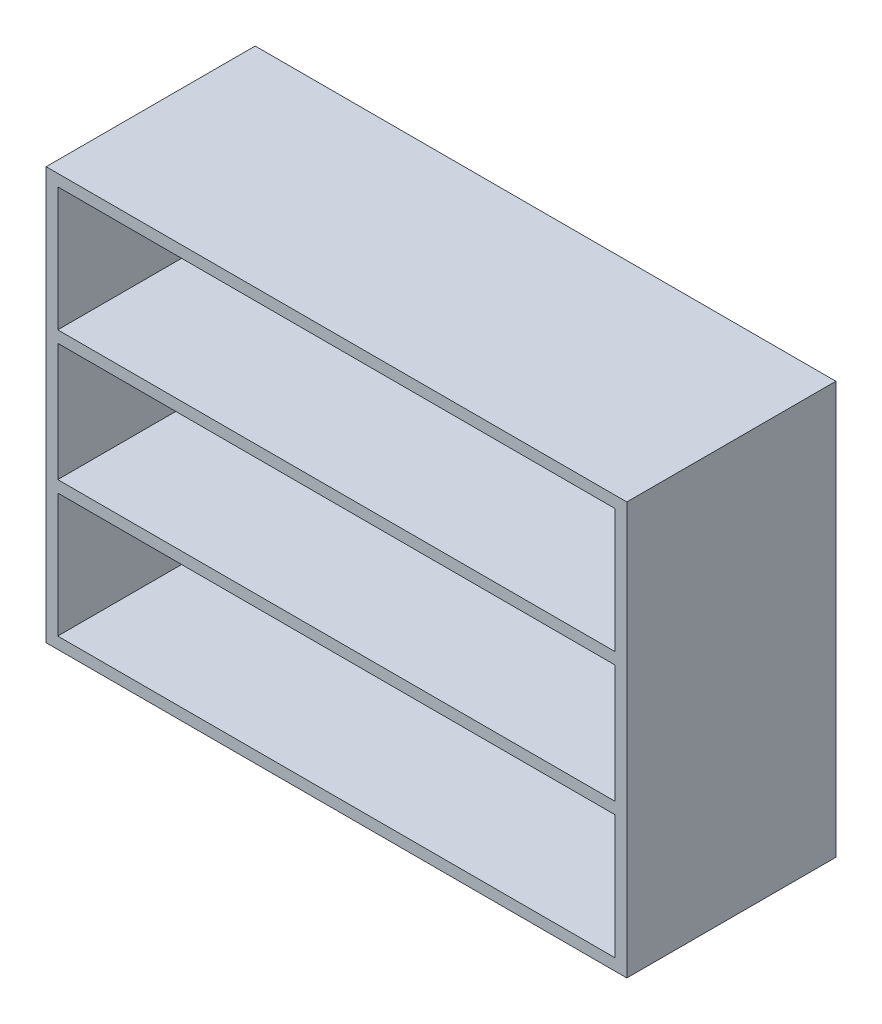
SolidWorks part; units mm, degrees
ref_plane "Front" through (0, 0, 0) normal (0, 0, 1) x (1, 0, 0)
ref_plane "Top" through (0, 0, 0) normal (0, 1, 0) x (1, 0, 0)
ref_plane "Right" through (0, 0, 0) normal (1, 0, 0) x (0, 0, -1)
sketch "Sketch1" plane through (0, 0, 0) normal (0, 1, 0) x (1, 0, 0)
  line L1 (-1270, 457.2) -> (1270, 457.2)
  line L2 (-1270, 457.2) -> (-1270, -457.2)
  line L3 (-1270, -457.2) -> (1270, -457.2)
  line L4 (1270, 457.2) -> (1270, -457.2)
  line L5 (-1270, 457.2) -> (1270, -457.2) construction
  line L6 (-1270, -457.2) -> (1270, 457.2) construction
  point P0 (0, 0)
  dimension "D1" = 2540
  dimension "D2" = 914.4
extrude "Boss-Extrude1" add sketch "Sketch1" along normal blind 1803.4
sketch "Sketch2" plane through (0, 0, 457.2) normal (0, 0, 1) x (1, 0, 0)
  line L0 (-1219.2, 50.8) -> (1219.2, 50.8)
  line L1 (1219.2, 50.8) -> (1219.2, 592.6667)
  line L2 (1219.2, 1752.6) -> (-1219.2, 1752.6)
  line L3 (-1219.2, 1752.6) -> (-1219.2, 1210.7333)
  line L4 (-1270, 0) -> (1270, 0)
  line L5 (1270, 0) -> (1270, 1803.4)
  line L6 (1270, 1803.4) -> (-1270, 1803.4)
  line L7 (-1270, 1803.4) -> (-1270, 0)
  line L8 (-1270, 0) -> (1270, 0) construction
  line L9 (1270, 0) -> (1270, 1803.4) construction
  line L10 (1270, 1803.4) -> (-1270, 1803.4) construction
  line L11 (-1270, 1803.4) -> (-1270, 0) construction
  line L12 (-1219.2, 1185.3333) -> (1219.2, 1185.3333) construction
  line L13 (-1219.2, 618.0667) -> (1219.2, 618.0667) construction
  line L14 (0, 1185.3333) -> (0, 1752.6) construction
  line L15 (0, 1185.3333) -> (0, 618.0667) construction
  line L16 (0, 618.0667) -> (0, 50.8) construction
  line L17 (-1219.2, 1159.9333) -> (1219.2, 1159.9333)
  line L18 (-1219.2, 592.6667) -> (1219.2, 592.6667)
  line L19 (-1219.2, 1210.7333) -> (1219.2, 1210.7333)
  line L20 (-1219.2, 643.4667) -> (1219.2, 643.4667)
  line L21 (-1219.2, 1159.9333) -> (-1219.2, 643.4667)
  line L22 (-1219.2, 1752.6) -> (-1219.2, 50.8) construction
  line L23 (-1219.2, 592.6667) -> (-1219.2, 50.8)
  line L24 (1219.2, 643.4667) -> (1219.2, 1159.9333)
  line L25 (1219.2, 50.8) -> (1219.2, 1752.6) construction
  line L26 (1219.2, 1210.7333) -> (1219.2, 1752.6)
  dimension "D1" = 0
  dimension "D2" = 50.8
  dimension "D3" = 25.4
  dimension "D4" = 25.4
extrude "Cut-Extrude1" cut sketch "Sketch2" against normal through all
